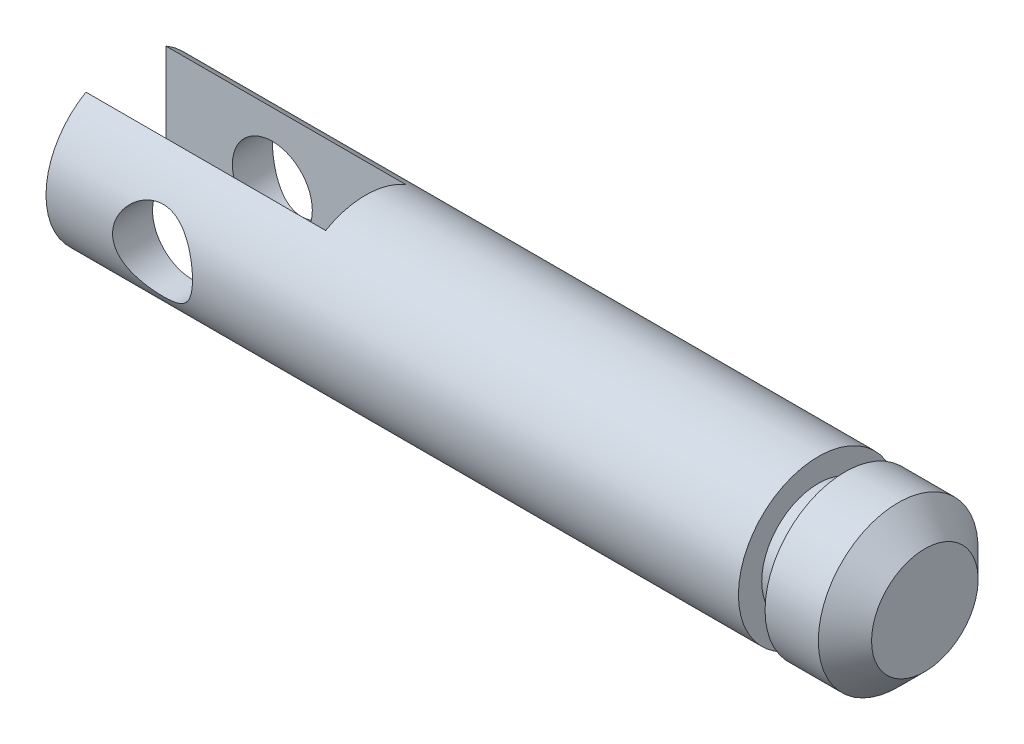
SolidWorks part; units mm, degrees
ref_plane "Front Plane" through (0, 0, 0) normal (0, 0, 1) x (1, 0, 0)
ref_plane "Top Plane" through (0, 0, 0) normal (0, 1, 0) x (1, 0, 0)
ref_plane "Right Plane" through (0, 0, 0) normal (1, 0, 0) x (0, 0, -1)
sketch "Sketch1" plane through (0, 0, 0) normal (0, 0, 1) x (1, 0, 0)
  line L0 (0, 0) -> (30, 0) construction
  line L1 (30, 0) -> (30, 2)
  line L2 (30, 2) -> (29, 3)
  line L3 (29, 3) -> (27, 3)
  line L4 (27, 3) -> (27, 2.125)
  line L5 (27, 2.125) -> (26, 2.125)
  line L6 (26, 2.125) -> (26, 3)
  line L7 (26, 3) -> (0, 3)
  line L8 (0, 3) -> (0, 0)
  line L9 (0, 0) -> (30, 0)
  dimension "D1" = 4.25
  dimension "D2" = 1
  dimension "D3" = 45
  dimension "D4" = 6
  dimension "D5" = 3
  dimension "D6" = 1
  dimension "D7" = 26
revolve "Revolve1" add sketch "Sketch1" angle 360 about L0
sketch "Sketch2" plane through (0, 0, 0) normal (0, 1, 0) x (1, 0, 0)
  line L0 (0, 3) -> (0, -3) construction
  line L1 (0, 1.5) -> (9, 1.5)
  line L2 (0, 1.5) -> (0, -1.5)
  line L3 (0, -1.5) -> (9, -1.5)
  line L4 (9, 1.5) -> (9, -1.5)
  point P6 (9, 0)
  dimension "D1" = 3
  dimension "D2" = 9
extrude "Cut-Extrude1" cut sketch "Sketch2" against normal through all both and the other way through all
sketch "Sketch3" plane through (0, 0, 0) normal (0, 0, 1) x (1, 0, 0)
  circle A0 centre (4, 0) radius 1.5
  dimension "D1" = 3
  dimension "D2" = 4
extrude "Cut-Extrude2" cut sketch "Sketch3" against normal through all both and the other way through all
